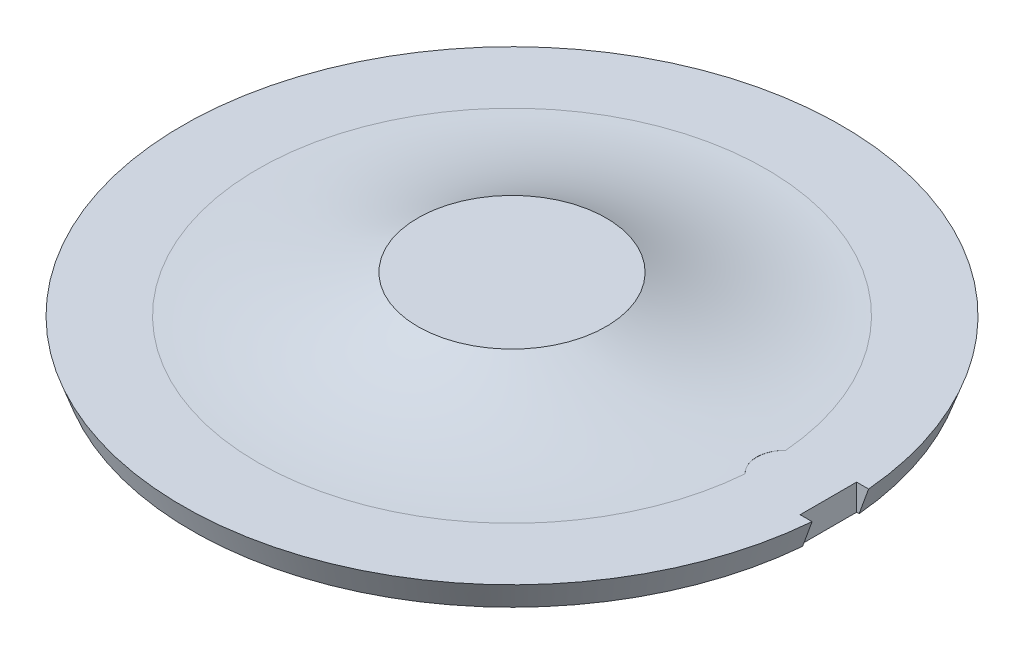
SolidWorks part; units mm, degrees
material "1060 Alloy"
ref_plane "Front Plane" through (0, 0, 0) normal (0, 0, 1) x (1, 0, 0)
ref_plane "Top Plane" through (0, 0, 0) normal (0, 1, 0) x (1, 0, 0)
ref_plane "Right Plane" through (0, 0, 0) normal (1, 0, 0) x (0, 0, -1)
sketch "Sketch2" plane through (0, 0, 0) normal (0, 0, 1) x (1, 0, 0)
  line L21 (431.7999, 0) -> (444.5, 35.2523)
  line L23 (0, 86.0523) -> (0, 0)
  line L26 (292.0999, 0) -> (431.7999, 0)
  line L32 (342.9, 35.2523) -> (444.5, 35.2523)
  line L33 (342.9, 35.2523) -> (0, 35.2523) construction
  line L36 (127, 86.0523) -> (0, 86.0523)
  line L39 (0, 0) -> (0, -50.8)
  line L40 (0, -50.8) -> (88.9, -50.8)
  line L42 (292.0999, 0) -> (0, 0) construction
  arc A0 (342.9, 35.2523) -> (127, 86.0523) centre (342.9, 519.4398) cw
  arc A2 (292.0999, 0) -> (88.9, -50.8) centre (292.0999, -431.7996) ccw
  point P15 (381, 0)
  dimension "D4" = 127
  dimension "D5" = 139.7
  dimension "D6" = 70.188
  dimension "D8" = 431.7999
  dimension "D10" = 431.7996
  dimension "D9" = 88.9
  dimension "D11" = 101.6
  dimension "D12" = 484.1875
  dimension "D2" = 86.0523
  dimension "D3" = 37.4702
revolve "Revolve3" add sketch "Sketch2" angle 360 about L23
ref_plane "Plane2" through (426.72, 0, 0) normal (1, 0, 0) x (0, 0, -1)
sketch "Sketch3" plane through (426.72, 0, 0) normal (1, 0, 0) x (0, 0, -1)
  line L0 (-38.1, 0) -> (38.1, 0)
  line L1 (-292.0999, 0) -> (292.0999, 0) construction
  line L2 (38.1, 0) -> (38.1, 35.2523)
  line L3 (444.5, 35.2523) -> (-444.5, 35.2523) construction
  line L4 (38.1, 35.2523) -> (-38.1, 35.2523)
  line L5 (-38.1, 35.2523) -> (-38.1, 0)
  point P6 (0, 0)
  dimension "D1" = 76.2
extrude "Cut-Extrude1" cut sketch "Sketch3" along normal through all
sketch "Sketch4" plane through (0, 35.2523, 0) normal (0, 1, 0) x (1, 0, 0)
  line L1 (426.72, -38.1) -> (368.3, -38.1)
  line L2 (426.72, -38.1) -> (426.72, 38.1)
  line L3 (426.72, 38.1) -> (368.3, 38.1)
  arc A0 (368.3, -38.1) -> (368.3, 38.1) centre (368.3, 0) cw
  dimension "D2" = 38.1
  dimension "D1" = 58.42
extrude "Cut-Extrude2" cut sketch "Sketch4" along normal through all
sketch "Sketch5" plane through (0, 0, 0) normal (0, -1, 0) x (1, 0, 0)
  line L1 (426.72, -38.1) -> (287.02, -38.1)
  line L2 (426.72, -38.1) -> (426.72, 38.1)
  line L3 (426.72, 38.1) -> (287.02, 38.1)
  arc A0 (287.02, -38.1) -> (287.02, 38.1) centre (287.02, 0) cw
  dimension "D1" = 76.2
  dimension "D2" = 139.7
extrude "Cut-Extrude3" cut sketch "Sketch5" along normal through all
